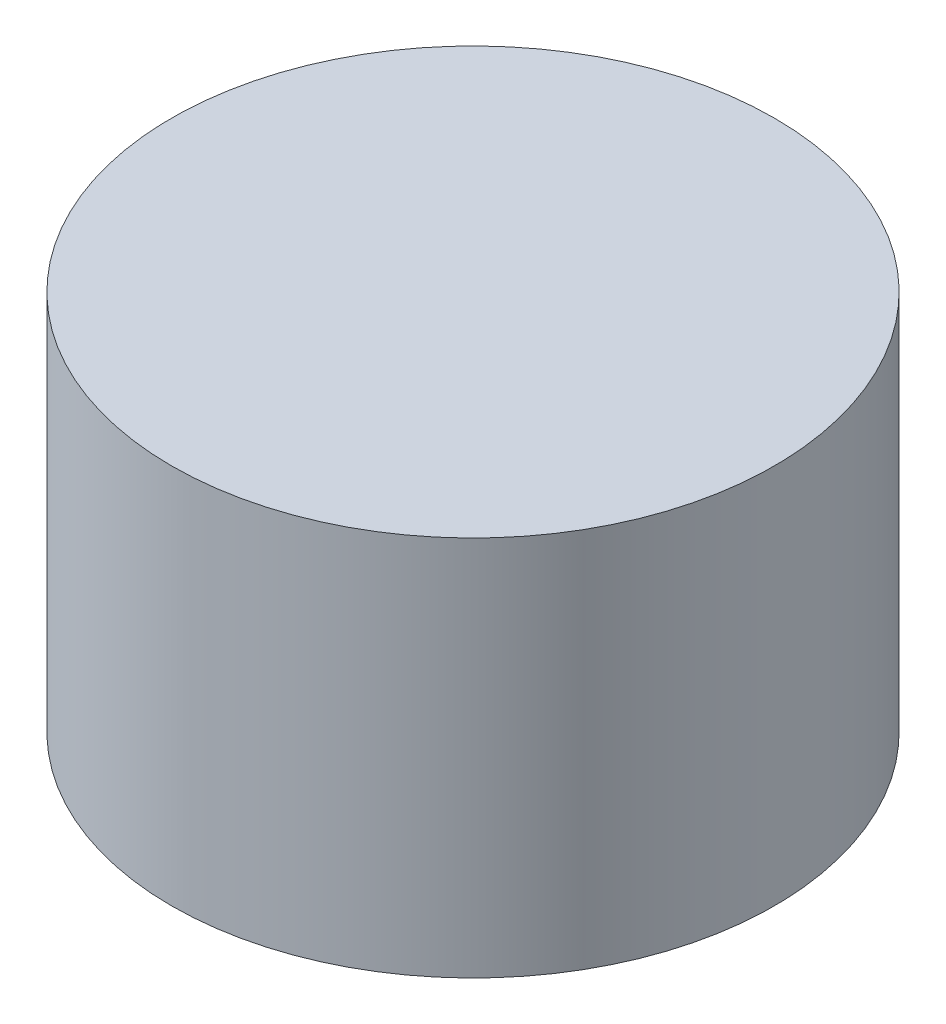
SolidWorks part; units mm, degrees
ref_plane "Front Plane" through (0, 0, 0) normal (0, 0, 1) x (1, 0, 0)
ref_plane "Top Plane" through (0, 0, 0) normal (0, 1, 0) x (1, 0, 0)
ref_plane "Right Plane" through (0, 0, 0) normal (1, 0, 0) x (0, 0, -1)
sketch "Sketch1" plane through (0, 0, 0) normal (0, 1, 0) x (1, 0, 0)
  circle A0 centre (0, 0) radius 111.5
  dimension "D1" = 223
extrude "Boss-Extrude1" add sketch "Sketch1" along normal blind 141
